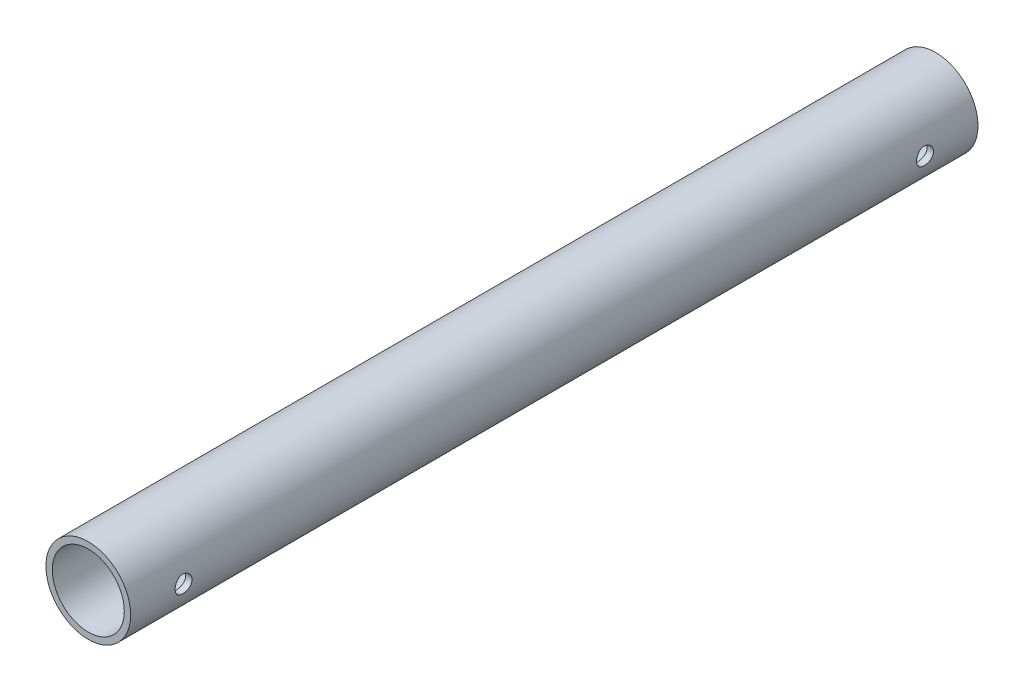
SolidWorks part; units mm, degrees
ref_plane "Front Plane" through (0, 0, 0) normal (0, 0, 1) x (1, 0, 0)
ref_plane "Top Plane" through (0, 0, 0) normal (0, 1, 0) x (1, 0, 0)
ref_plane "Right Plane" through (0, 0, 0) normal (1, 0, 0) x (0, 0, -1)
sketch "Sketch1" plane through (0, 0, 0) normal (0, 0, 1) x (1, 0, 0)
  circle A0 centre (0, 0) radius 8.5
  circle A1 centre (0, 0) radius 10
  dimension "D1" = 20
  dimension "D2" = 1.5
extrude "Boss-Extrude1" add sketch "Sketch1" along normal blind 100
sketch "Sketch2" plane through (0, 0, 0) normal (1, 0, 0) x (0, 0, -1)
  circle A0 centre (-12.5, 0) radius 2
  dimension "D1" = 4
  dimension "D2" = 12.5
extrude "Cut-Extrude1" cut sketch "Sketch2" against normal through all both and the other way through all
mirror "Mirror1" about plane through (0, 0, 100) normal (0, 0, 1) of "Cut-Extrude1", "Boss-Extrude1"
